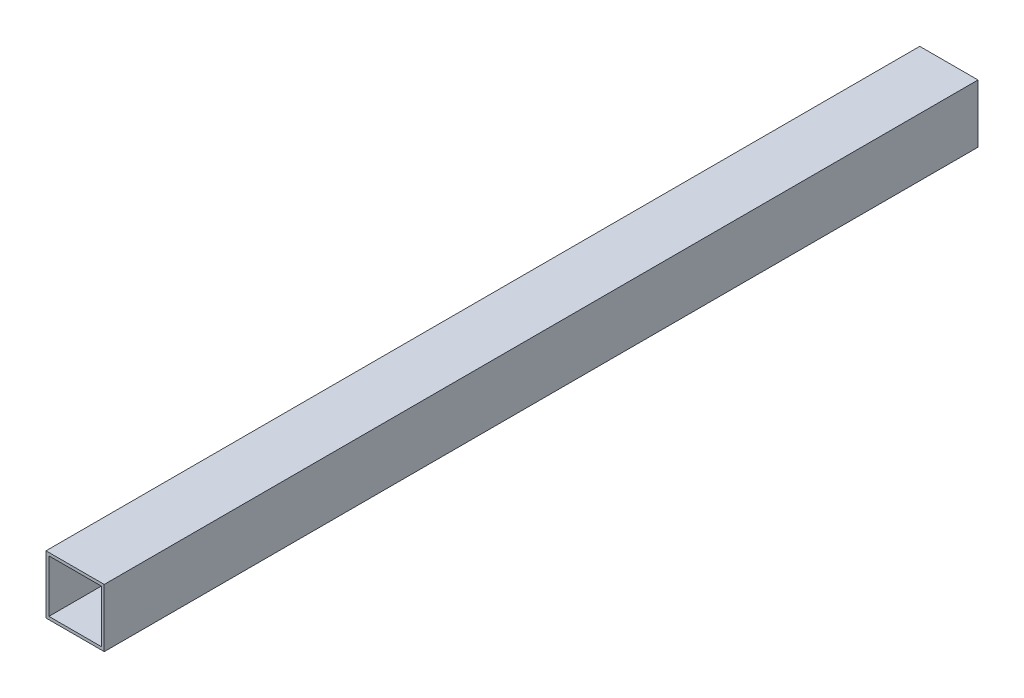
SolidWorks part; units mm, degrees
ref_plane "前视基准面" through (0, 0, 0) normal (0, 0, 1) x (1, 0, 0)
ref_plane "上视基准面" through (0, 0, 0) normal (0, 1, 0) x (1, 0, 0)
ref_plane "右视基准面" through (0, 0, 0) normal (1, 0, 0) x (0, 0, -1)
other "Configuration Table"
sketch "草图1" plane through (0, 0, 0) normal (0, 0, 1) x (1, 0, 0)
  line L0 (-9, 9) -> (9, 9)
  line L1 (-10, -10) -> (10, -10)
  line L2 (-10, -10) -> (-10, 10)
  line L3 (-10, 10) -> (10, 10)
  line L4 (10, -10) -> (10, 10)
  line L5 (-10, -10) -> (10, 10) construction
  line L6 (-10, 10) -> (10, -10) construction
  line L7 (9, -9) -> (9, 9)
  line L8 (-9, -9) -> (9, -9)
  line L9 (-9, -9) -> (-9, 9)
  point P0 (0, 0)
  dimension "D1" = 20
  dimension "D2" = 20
  dimension "D3" = 1
extrude "凸台-拉伸1" add sketch "草图1" along normal blind 150
sketch "草图2" plane through (0, 0, 150) normal (0, 0, 1) x (1, 0, 0)
  line L1 (-10, 10) -> (10, 10)
  line L2 (-10, 10) -> (-10, -10)
  line L3 (-10, -10) -> (10, -10)
  line L4 (10, 10) -> (10, -10)
  line L5 (-9, 9) -> (9, 9)
  line L6 (-9, 9) -> (-9, -9)
  line L7 (-9, -9) -> (9, -9)
  line L8 (9, 9) -> (9, -9)
extrude "凸台-拉伸2" add sketch "草图2" along normal blind 150
